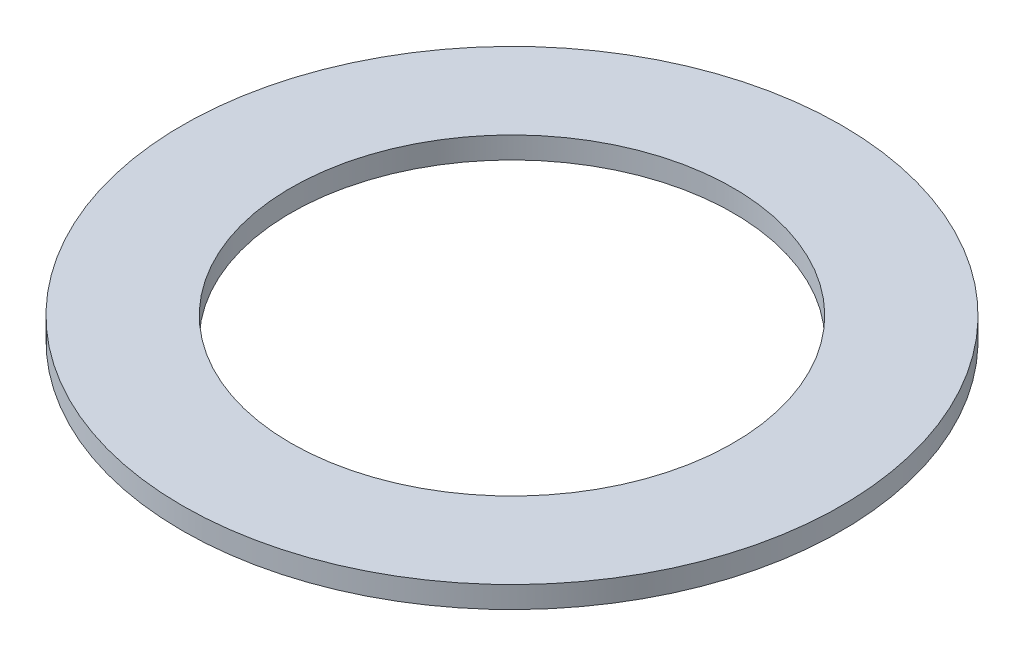
SolidWorks part; units mm, degrees
ref_plane "Front Plane" through (0, 0, 0) normal (0, 0, 1) x (1, 0, 0)
ref_plane "Top Plane" through (0, 0, 0) normal (0, 1, 0) x (1, 0, 0)
ref_plane "Right Plane" through (0, 0, 0) normal (1, 0, 0) x (0, 0, -1)
sketch "Sketch1" plane through (0, 0, 0) normal (0, 1, 0) x (1, 0, 0)
  circle A0 centre (0, 0) radius 7.6
  circle A1 centre (0, 0) radius 5.1
extrude "Boss-Extrude1" add sketch "Sketch1" along normal blind 0.5
